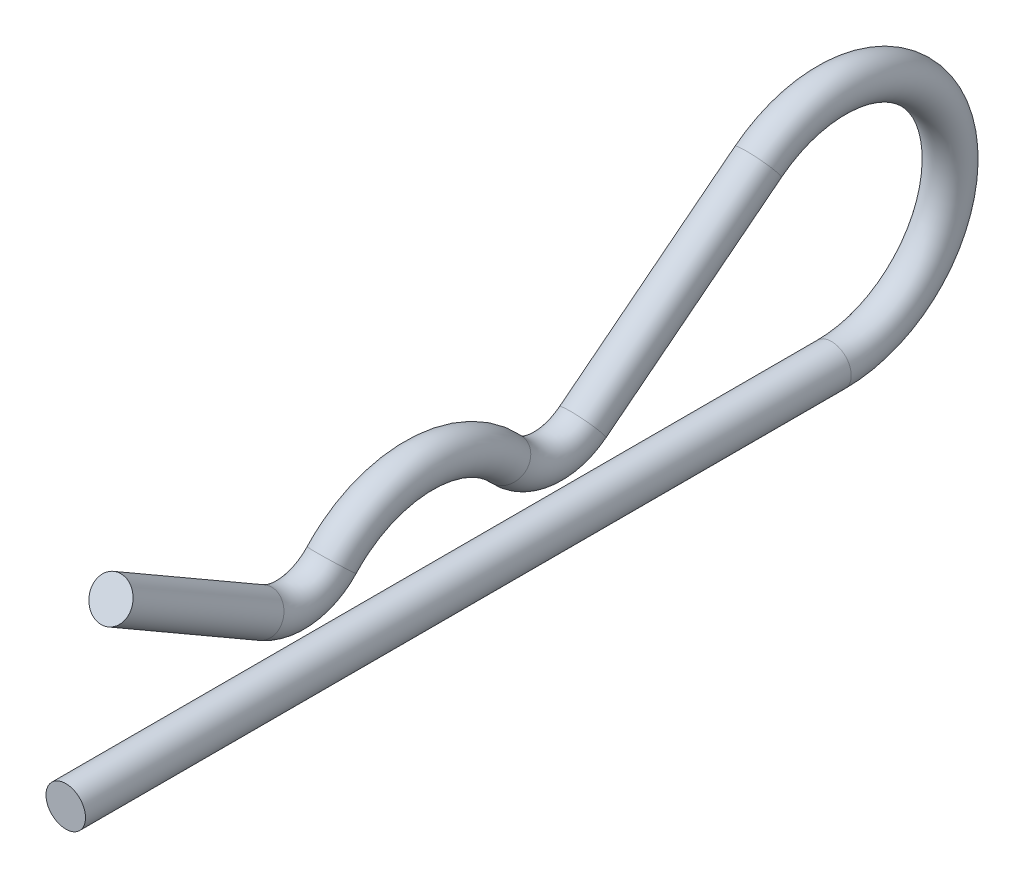
SolidWorks part; units mm, degrees
ref_plane "Front" through (0, 0, 0) normal (0, 0, 1) x (1, 0, 0)
ref_plane "Top" through (0, 0, 0) normal (0, 1, 0) x (1, 0, 0)
ref_plane "Right" through (0, 0, 0) normal (1, 0, 0) x (0, 0, -1)
sketch "Sketch1" plane through (0, 0, 0) normal (0, 0, 1) x (1, 0, 0)
  circle A0 centre (0, 0) radius 1
sketch "Sketch2" plane through (0, 0, 0) normal (1, 0, 0) x (0, 0, -1)
  line L0 (0, 0) -> (38.72, 0)
  line L1 (11.3447, 6) -> (24.3753, 6) construction
  line L2 (45.72, 0) -> (45.72, 6) construction
  line L3 (45.72, 6) -> (44.72, 6) construction
  line L5 (45.72, 0) -> (0, 0) construction
  line L6 (9.9161, 3.5256) -> (2.286, 7.9309)
  line L7 (17.86, 6) -> (17.86, 0) construction
  line L13 (35.0153, 10.7197) -> (26.1394, 3.7525)
  circle A0 centre (38.72, 6) radius 5 construction
  arc A1 (22.2736, 4.0645) -> (13.4464, 4.0645) centre (17.86, 0) ccw
  arc A6 (13.4464, 4.0645) -> (9.9161, 3.5256) centre (11.3447, 6) cw
  arc A8 (26.1394, 3.7525) -> (22.2736, 4.0645) centre (24.3753, 6) cw
  arc A9 (38.72, 0) -> (35.0153, 10.7197) centre (38.72, 6) ccw
  dimension "D1" = 2.8571
  dimension "D2" = 17.86
  dimension "D5" = 2.286
  dimension "D9" = 30
  dimension "D11" = 1
  dimension "D3" = 1
sweep "Sweep1" add profiles "Sketch1" path "Sketch2"
equation "\"D11@Sketch2\" = \"WireOD@Sketch1\"/2"
equation "\"D1@Sketch2\"=\"EyeID@Sketch2\"/3.5"
equation "\"D3@Sketch2\" = \"D11@Sketch2\""
equation "\"D2@Sketch2\" = (\"Length@Sketch2\"-\"EyeID@Sketch2\")/2"
equation "\"D5@Sketch2\" = \"Length@Sketch2\"*.05"
